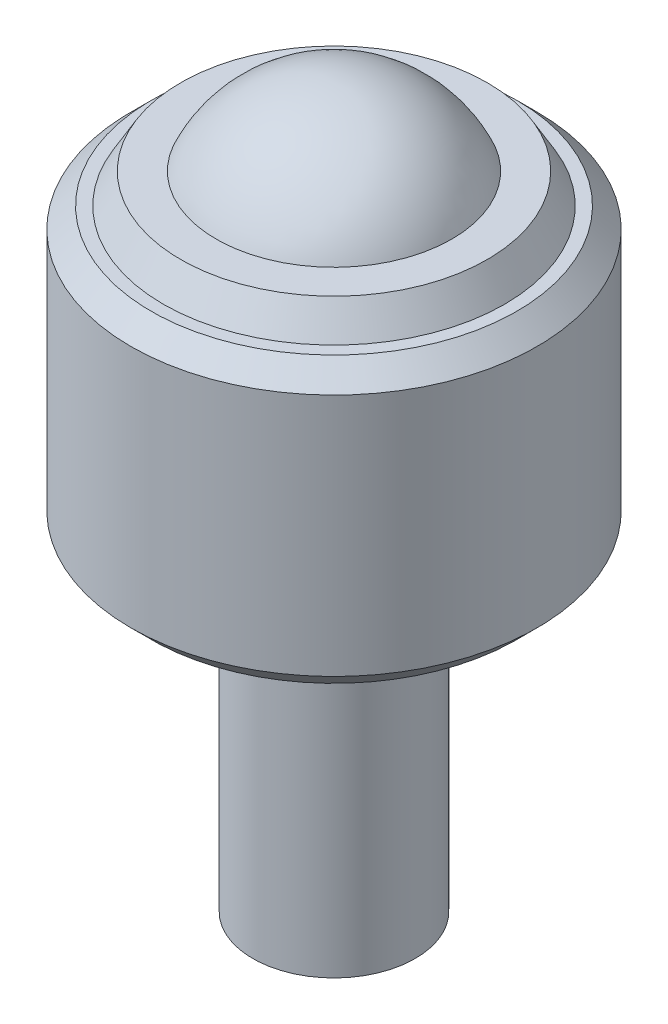
SolidWorks part; units mm, degrees
ref_plane "Front Plane" through (0, 0, 0) normal (0, 0, 1) x (1, 0, 0)
ref_plane "Top Plane" through (0, 0, 0) normal (0, 1, 0) x (1, 0, 0)
ref_plane "Right Plane" through (0, 0, 0) normal (1, 0, 0) x (0, 0, -1)
sketch "Sketch1" plane through (0, 0, 0) normal (0, 0, 1) x (1, 0, 0)
  line L0 (-0.174, 0) -> (-0.174, 29.1702) construction
  line L1 (5.6283, 36.7546) -> (7.3721, 36.7546)
  line L2 (7.3721, 36.7546) -> (8.226, 35.2746)
  line L3 (8.226, 35.2746) -> (8.826, 35.2746)
  line L4 (9.826, 34.2746) -> (9.826, 22.2746)
  line L5 (9.826, 22.2746) -> (8.826, 21.2746)
  line L6 (8.826, 35.2746) -> (9.826, 34.2746)
  line L7 (8.826, 21.2746) -> (4.826, 21.2746)
  line L8 (3.826, 20.2746) -> (3.826, 5.1746)
  line L9 (3.826, 5.1746) -> (-0.174, 5.1746)
  line L10 (-0.174, 40.5246) -> (3.4583, 40.5246) construction
  line L11 (-0.174, 40.5246) -> (-0.174, 5.1746)
  arc A0 (5.6283, 36.7546) -> (-0.174, 40.5246) centre (-0.174, 34.1746) ccw
  arc A1 (3.826, 20.2746) -> (4.826, 21.2746) centre (4.826, 20.2746) cw
  point P9 (9.826, 35.2746)
  point P11 (9.826, 21.2746)
  dimension "D1" = 12.7
  dimension "D8" = 1
  dimension "D2" = 20
  dimension "D3" = 16.8
  dimension "D4" = 3.77
  dimension "D5" = 5.25
  dimension "D6" = 19.25
  dimension "D7" = 16.1
  dimension "D9" = 4
revolve "Revolve1" add sketch "Sketch1" angle 360 about L0
